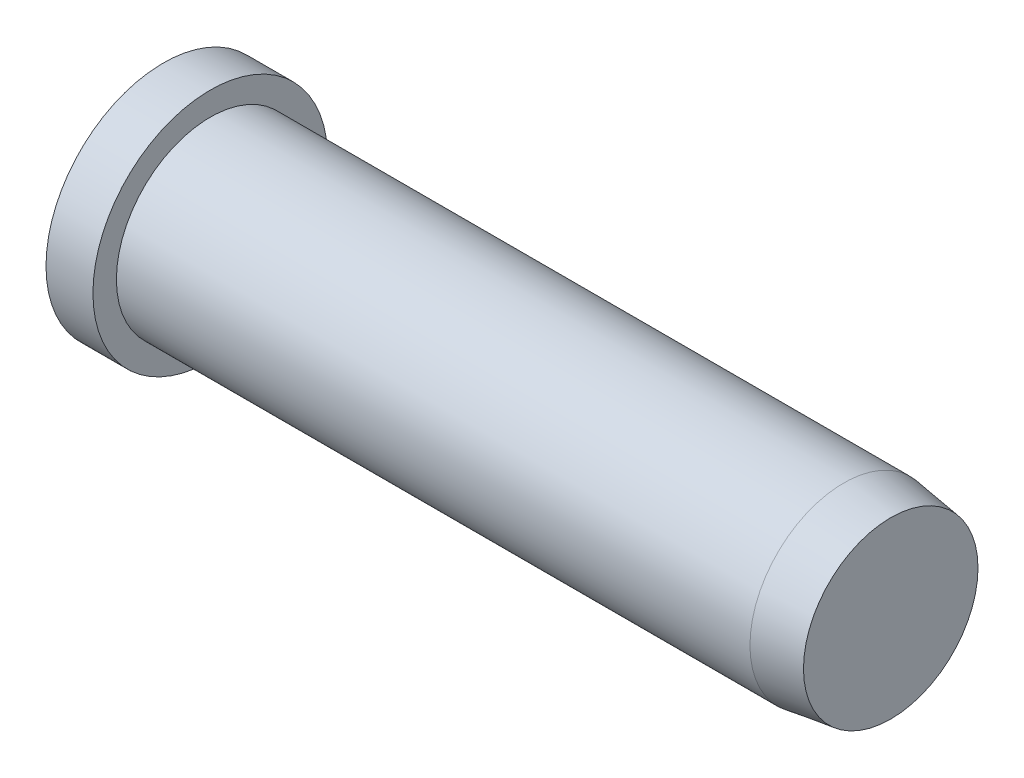
SolidWorks part; units mm, degrees
ref_plane "Front Plane" through (0, 0, 0) normal (0, 0, 1) x (1, 0, 0)
ref_plane "Top Plane" through (0, 0, 0) normal (0, 1, 0) x (1, 0, 0)
ref_plane "Right Plane" through (0, 0, 0) normal (1, 0, 0) x (0, 0, -1)
sketch "Sketch1" plane through (0, 0, 0) normal (0, 1, 0) x (1, 0, 0)
  line L0 (0, 0) -> (155, 0)
  line L1 (155, 0) -> (155, 20)
  line L2 (155, 20) -> (10, 20)
  line L3 (10, 20) -> (10, 25)
  line L4 (10, 25) -> (0, 25)
  line L5 (0, 25) -> (0, 0)
revolve "Revolve1" add sketch "Sketch1" angle 360 about L0
chamfer "Chamfer1" distance 10 angle 8 1 edges at (155, 0, 20)
sketch "Sketch2" plane through (0, 0, 0) normal (-1, 0, 0) x (0, 0, 1)
  point P0 (0, 0)
